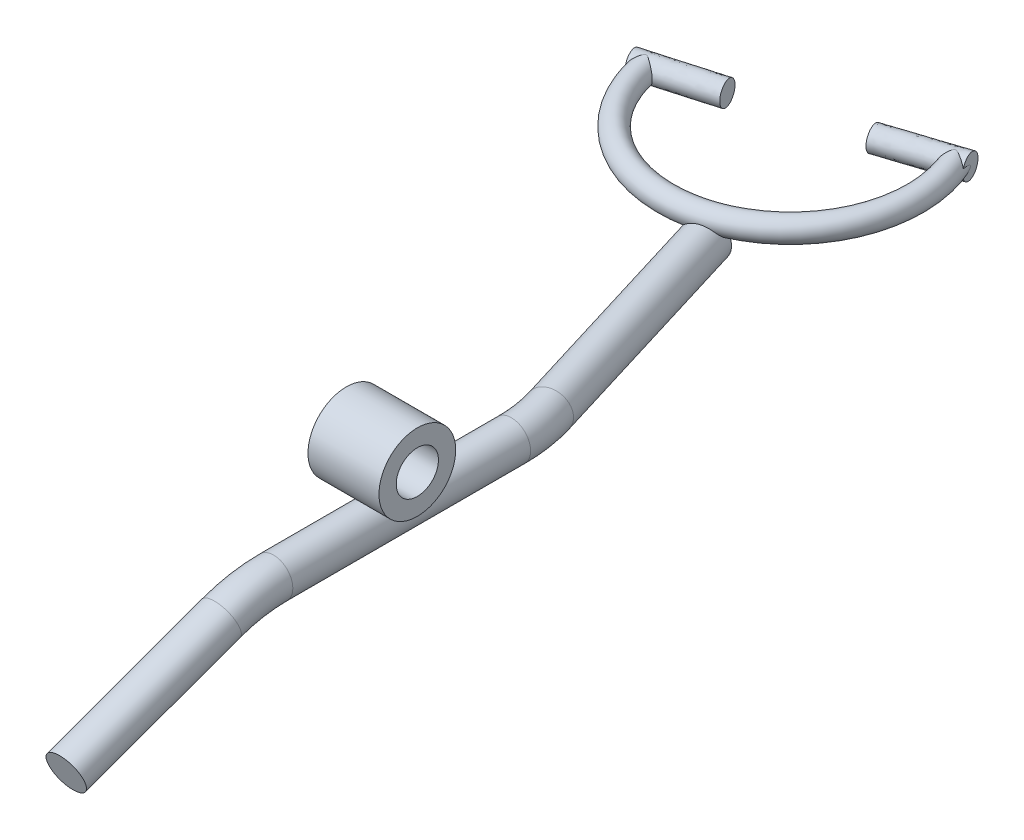
SolidWorks part; units mm, degrees
ref_plane "Спереди" through (0, 0, 0) normal (0, 0, 1) x (1, 0, 0)
ref_plane "Сверху" through (0, 0, 0) normal (0, 1, 0) x (1, 0, 0)
ref_plane "Справа" through (0, 0, 0) normal (1, 0, 0) x (0, 0, -1)
sketch "Эскиз1" plane through (0, 0, 0) normal (1, 0, 0) x (0, 0, -1)
  circle A0 centre (0, 0) radius 5.5
  circle A1 centre (0, 0) radius 10
  dimension "D1" = 20
  dimension "D2" = 11
extrude "Бобышка-Вытянуть1" add sketch "Эскиз1" along normal blind 18.5
ref_plane "Плоскость1" through (9.25, 0, 0) normal (1, 0, 0) x (0, 0, -1)
sketch3d "Трехмерный эскиз1"
  line L0 (9, -14.5, 27.9469) -> (9, -14.5, -34.022)
  line L1 (0, -14.5, 35) -> (9, -14.5, 35) construction
  line L2 (0, 0, 0) -> (0, 0, 35) construction
  line L3 (0, 0, 35) -> (0, -14.5, 35) construction
  line L4 (9, -16.9123, 41.6277) -> (9, -31.601, 81.9846)
  line L5 (7.2522, -14.5, -45.7168) -> (-10.8813, -14.5, -105.0287)
  arc A0 (9, -14.5, -34.022) -> (7.2522, -14.5, -45.7168) centre (-31, -14.5, -34.022) ccw
  arc A1 (9, -14.5, 27.9469) -> (9, -16.9123, 41.6277) centre (9, -54.5, 27.9469) ccw
  point P11 (9, -14.5, -40)
  point P13 (-31, 25.5, -34.022)
  point P16 (9, -14.5, 35)
  point P18 (49, -54.5, 27.9469)
  dimension "D9" = 40
  dimension "D1" = 75
  dimension "D2" = 14.5
  dimension "D4" = 9
  dimension "D3" = 35
  dimension "D5" = 160
  dimension "D6" = 50
  dimension "D7" = 163
  dimension "D8" = 68
sketch "Эскиз4" plane through (0, 0, 0) normal (0, 0, 1) x (1, 0, 0)
  circle A0 centre (9, -14.5) radius 5
  dimension "D1" = 10
sweep "По траектории1" add profiles "Эскиз4" path "Трехмерный эскиз1"
ref_plane "Плоскость2" through (0, -9.5, 0) normal (0, 1, 0) x (1, 0, 0)
sketch "Эскиз5" plane through (0, -9.5, 0) normal (0, 1, 0) x (1, 0, 0)
  line L0 (-10.8813, 105.0287) -> (-21.54, 139.8918) construction
  line L1 (-6.0998, 106.4906) -> (-15.6628, 103.5669) construction
  line L2 (-52.4071, 130.4547) -> (9.3271, 149.3288) construction
  arc A0 (9.3271, 149.3288) -> (-52.4071, 130.4547) centre (-20.3883, 136.1248) cw
  point P7 (-10.8813, 105.0287)
  point P11 (-21.54, 139.8918)
ref_plane "Плоскость3" through (-52.4071, -9.5, -130.4547) normal (-0.1744, 0, -0.9847) x (-0.9847, 0, 0.1744)
sketch "Эскиз6" plane through (-52.4071, -9.5, -130.4547) normal (-0.1744, 0, -0.9847) x (-0.9847, 0, 0.1744)
  circle A0 centre (0, 0) radius 3
  dimension "D1" = 6
sweep "По траектории2" add profiles "Эскиз6" path "Эскиз5"
sketch "Эскиз7" plane through (0, -9.5, 0) normal (0, 1, 0) x (1, 0, 0)
  line L1 (-52.4071, 130.4547) -> (9.3271, 149.3288) construction
  line L2 (-6.948, 144.353) -> (12.0686, 150.547)
  dimension "D1" = 20
ref_plane "Плоскость4" through (-6.948, -9.5, -144.353) normal (0.9563, 0, -0.2924) x (-0.2924, 0, -0.9563)
sketch "Эскиз8" plane through (-6.948, -9.5, -144.353) normal (0.9563, 0, -0.2924) x (-0.2924, 0, -0.9563)
  circle A0 centre (0, 0) radius 3
  dimension "D1" = 6
sweep "По траектории4" add profiles "Эскиз8" path "Эскиз7"
sketch "Эскиз9" plane through (0, -9.5, 0) normal (0, 1, 0) x (1, 0, 0)
  line L0 (-36.1319, 135.4305) -> (-55.3611, 129.9316)
  line L1 (-52.4071, 130.4547) -> (9.3271, 149.3288) construction
  dimension "D1" = 20
ref_plane "Плоскость5" through (-36.1319, -9.5, -135.4305) normal (0.9563, 0, -0.2924) x (-0.2924, 0, -0.9563)
sketch "Эскиз10" plane through (-36.1319, -9.5, -135.4305) normal (0.9563, 0, -0.2924) x (-0.2924, 0, -0.9563)
  circle A0 centre (0, 0) radius 3
  dimension "D1" = 6
sweep "По траектории5" add profiles "Эскиз10" path "Эскиз9"
